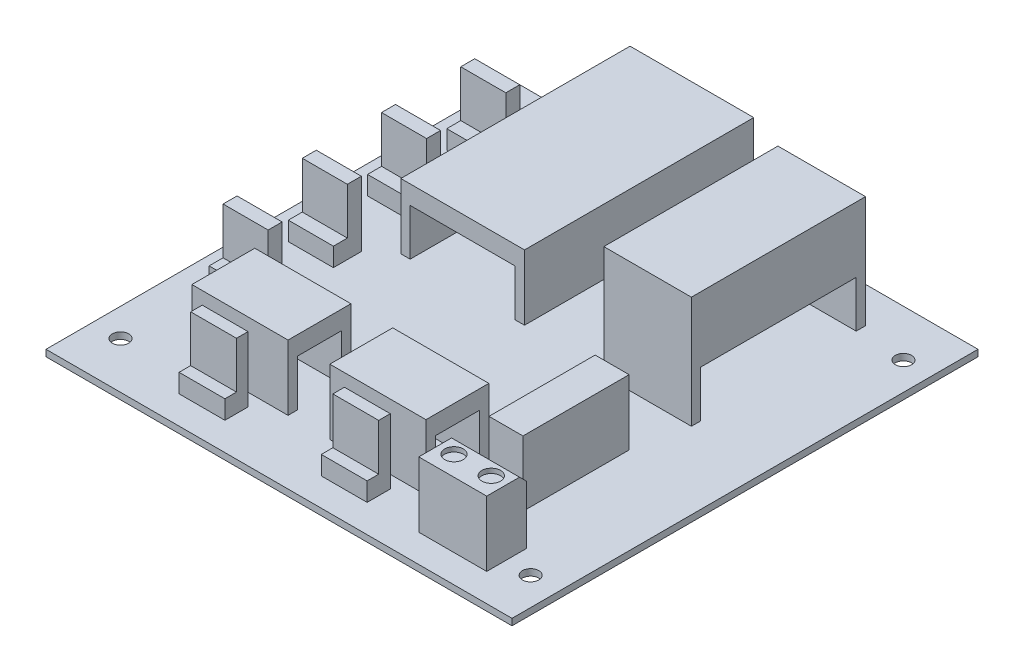
SolidWorks part; units mm, degrees
ref_plane "Plano frontal" through (0, 0, 0) normal (0, 0, 1) x (1, 0, 0)
ref_plane "Plano superior" through (0, 0, 0) normal (0, 1, 0) x (1, 0, 0)
ref_plane "Plano direito" through (0, 0, 0) normal (1, 0, 0) x (0, 0, -1)
sketch "Esboço1" plane through (0, 0, 0) normal (0, 1, 0) x (1, 0, 0)
  line L1 (50, -50) -> (-50, -50)
  line L2 (50, -50) -> (50, 50)
  line L3 (50, 50) -> (-50, 50)
  line L4 (-50, -50) -> (-50, 50)
  line L5 (50, -50) -> (-50, 50) construction
  line L6 (50, 50) -> (-50, -50) construction
  point P0 (0, 0)
  dimension "D1" = 100
extrude "Ressalto-extrusão1" add sketch "Esboço1" along normal blind 1.4
sketch "Esboço2" plane through (0, 1.4, 0) normal (0, 1, 0) x (1, 0, 0)
  line L0 (-50, 50) -> (-50, -50) construction
  line L1 (44, -44) -> (-44, -44)
  line L2 (44, -44) -> (44, 44)
  line L3 (44, 44) -> (-44, 44)
  line L4 (-44, -44) -> (-44, 44)
  line L5 (44, -44) -> (-44, 44) construction
  line L6 (44, 44) -> (-44, -44) construction
  line L7 (-50, -50) -> (50, -50) construction
  point P0 (0, 0)
  dimension "D1" = 6
  dimension "D2" = 6
extrude "Ressalto-extrusão2" add sketch "Esboço2" along normal blind 24
sketch "Esboço4" plane through (0, 25.4, 0) normal (0, 1, 0) x (1, 0, 0)
  line L0 (-44, -44) -> (44, -44) construction
  line L1 (38.5727, -44) -> (23.994, -44)
  line L2 (38.5727, -44) -> (38.5727, -35.4595)
  line L3 (38.5727, -35.4595) -> (23.994, -35.4595)
  line L4 (23.994, -44) -> (23.994, -35.4595)
  line L6 (23.994, -6.1504) -> (31.2833, -6.1504)
  line L7 (23.994, -6.1504) -> (23.994, -28.9295)
  line L8 (23.994, -28.9295) -> (31.2833, -28.9295)
  line L9 (31.2833, -6.1504) -> (31.2833, -28.9295)
  line L14 (14.7668, 42.2996) -> (33.5612, 42.2996)
  line L15 (14.7668, 42.2996) -> (14.7668, 4.9355)
  line L16 (14.7668, 4.9355) -> (33.5612, 4.9355)
  line L17 (33.5612, 42.2996) -> (33.5612, 4.9355)
  line L18 (-29.6701, 44) -> (-3.1234, 44)
  line L19 (-29.6701, 44) -> (-29.6701, 5.8111)
  line L20 (-29.6701, 5.8111) -> (-3.1234, 5.8111)
  line L21 (-3.1234, 44) -> (-3.1234, 5.8111)
  line L22 (44, 44) -> (-44, 44) construction
  line L23 (-32.3794, -22.8163) -> (-11.7467, -22.8163)
  line L24 (-32.3794, -22.8163) -> (-32.3794, -36.3118)
  line L25 (-32.3794, -36.3118) -> (-11.7467, -36.3118)
  line L26 (-11.7467, -22.8163) -> (-11.7467, -36.3118)
  line L27 (-2.7851, -22.8163) -> (17.8476, -22.8163)
  line L28 (-2.7851, -22.8163) -> (-2.7851, -36.3118)
  line L29 (-2.7851, -36.3118) -> (17.8476, -36.3118)
  line L30 (17.8476, -22.8163) -> (17.8476, -36.3118)
  line L31 (-44, 44) -> (-44, -44) construction
  line L32 (-50, 50) -> (50, 50)
  line L33 (-50, 50) -> (-50, -50)
  line L34 (-50, -50) -> (50, -50)
  line L35 (50, 50) -> (50, -50)
  line L36 (-44, 36) -> (-34.3294, 36)
  line L37 (-44, 36) -> (-44, 30)
  line L38 (-44, 30) -> (-34.3294, 30)
  line L39 (-34.3294, 36) -> (-34.3294, 30)
  line L40 (-44, 19) -> (-34.3294, 19)
  line L41 (-34.3294, 19) -> (-34.3294, 13)
  line L42 (-44, 13) -> (-34.3294, 13)
  line L43 (-44, 19) -> (-44, 13)
  line L44 (-44, 2) -> (-34.3294, 2)
  line L45 (-34.3294, 2) -> (-34.3294, -4)
  line L46 (-44, -4) -> (-34.3294, -4)
  line L47 (-44, 2) -> (-44, -4)
  line L48 (-44, -15) -> (-34.3294, -15)
  line L49 (-34.3294, -15) -> (-34.3294, -21)
  line L50 (-44, -21) -> (-34.3294, -21)
  line L51 (-44, -15) -> (-44, -21)
  line L52 (-44, -44) -> (44, -44) construction
  line L53 (-27.4417, -39.0319) -> (-17.6077, -39.0319)
  line L54 (-27.4417, -39.0319) -> (-27.4417, -44)
  line L55 (-27.4417, -44) -> (-17.6077, -44)
  line L56 (-17.6077, -39.0319) -> (-17.6077, -44)
  line L57 (-11.7467, -36.3118) -> (-2.7851, -36.3118) construction
  line L58 (-7.2659, -36.3118) -> (-7.2659, -44) construction
  line L59 (12.9099, -39.0319) -> (12.9099, -44)
  line L60 (12.9099, -44) -> (3.0759, -44)
  line L61 (3.0759, -39.0319) -> (3.0759, -44)
  line L62 (12.9099, -39.0319) -> (3.0759, -39.0319)
  line L63 (44, 44) -> (-44, 44) construction
  dimension "D1" = 4
  dimension "D2" = 8
  dimension "D3" = 6
  dimension "D4" = 11
extrude "Corte-extrusão1" cut sketch "Esboço4" against normal up to surface (24 mm away) up to face at (0, 1.4, 0)
sketch "Esboço5" plane through (0, 25.4, 0) normal (0, 1, 0) x (1, 0, 0)
  line L0 (23.994, -6.1504) -> (23.994, -28.9295) construction
  line L5 (23.994, -28.9295) -> (31.2833, -28.9295) construction
  line L6 (31.2833, -28.9295) -> (31.2833, -6.1504) construction
  line L7 (31.2833, -6.1504) -> (23.994, -6.1504) construction
  line L8 (-29.6701, 5.8111) -> (-3.1234, 5.8111)
  line L9 (-3.1234, 5.8111) -> (-3.1234, 44)
  line L10 (-3.1234, 44) -> (-29.6701, 44)
  line L11 (-29.6701, 44) -> (-29.6701, 5.8111)
  line L12 (-29.6701, 5.8111) -> (-3.1234, 5.8111)
  line L13 (-3.1234, 5.8111) -> (-3.1234, 44)
  line L14 (-3.1234, 44) -> (-29.6701, 44)
  line L15 (-29.6701, 44) -> (-29.6701, 5.8111)
  line L16 (-2.7851, -22.8163) -> (-2.7851, -36.3118) construction
  line L17 (-2.7851, -36.3118) -> (17.8476, -36.3118) construction
  line L18 (17.8476, -36.3118) -> (17.8476, -22.8163) construction
  line L19 (17.8476, -22.8163) -> (-2.7851, -22.8163) construction
  line L20 (-32.3794, -22.8163) -> (-32.3794, -36.3118) construction
  line L21 (-32.3794, -36.3118) -> (-11.7467, -36.3118) construction
  line L22 (-11.7467, -36.3118) -> (-11.7467, -22.8163) construction
  line L23 (-11.7467, -22.8163) -> (-32.3794, -22.8163) construction
  line L24 (23.994, -6.1504) -> (23.994, -28.9295)
  line L25 (23.994, -28.9295) -> (31.2833, -28.9295)
  line L26 (31.2833, -28.9295) -> (31.2833, -6.1504)
  line L27 (31.2833, -6.1504) -> (23.994, -6.1504)
  line L28 (-2.7851, -22.8163) -> (-2.7851, -36.3118)
  line L29 (-2.7851, -36.3118) -> (17.8476, -36.3118)
  line L30 (17.8476, -36.3118) -> (17.8476, -22.8163)
  line L31 (17.8476, -22.8163) -> (-2.7851, -22.8163)
  line L32 (-32.3794, -22.8163) -> (-32.3794, -36.3118)
  line L33 (-32.3794, -36.3118) -> (-11.7467, -36.3118)
  line L34 (-11.7467, -36.3118) -> (-11.7467, -22.8163)
  line L35 (-11.7467, -22.8163) -> (-32.3794, -22.8163)
  line L36 (-44, -15) -> (-44, -21) construction
  line L37 (-44, -21) -> (-34.3294, -21) construction
  line L38 (-34.3294, -21) -> (-34.3294, -15) construction
  line L39 (-34.3294, -15) -> (-44, -15) construction
  line L40 (38.5727, -35.4595) -> (23.994, -35.4595)
  line L41 (23.994, -35.4595) -> (23.994, -44)
  line L42 (23.994, -44) -> (38.5727, -44)
  line L43 (38.5727, -44) -> (38.5727, -35.4595)
  line L44 (38.5727, -35.4595) -> (23.994, -35.4595)
  line L45 (23.994, -35.4595) -> (23.994, -44)
  line L46 (23.994, -44) -> (38.5727, -44)
  line L47 (38.5727, -44) -> (38.5727, -35.4595)
  line L48 (-44, 2) -> (-44, -4) construction
  line L49 (-44, -4) -> (-34.3294, -4) construction
  line L50 (-34.3294, -4) -> (-34.3294, 2) construction
  line L51 (-34.3294, 2) -> (-44, 2) construction
  line L52 (-44, 19) -> (-44, 13) construction
  line L53 (-44, 13) -> (-34.3294, 13) construction
  line L54 (-34.3294, 13) -> (-34.3294, 19) construction
  line L55 (-34.3294, 19) -> (-44, 19) construction
  line L56 (-44, 36) -> (-44, 30) construction
  line L57 (-44, 30) -> (-34.3294, 30) construction
  line L58 (-34.3294, 30) -> (-34.3294, 36) construction
  line L59 (-34.3294, 36) -> (-44, 36) construction
  line L60 (-44, -15) -> (-44, -21)
  line L61 (-44, -21) -> (-34.3294, -21)
  line L62 (-34.3294, -21) -> (-34.3294, -15)
  line L63 (-34.3294, -15) -> (-44, -15)
  line L64 (-44, 2) -> (-44, -4)
  line L65 (-44, -4) -> (-34.3294, -4)
  line L66 (-34.3294, -4) -> (-34.3294, 2)
  line L67 (-34.3294, 2) -> (-44, 2)
  line L68 (-44, 19) -> (-44, 13)
  line L69 (-44, 13) -> (-34.3294, 13)
  line L70 (-34.3294, 13) -> (-34.3294, 19)
  line L71 (-34.3294, 19) -> (-44, 19)
  line L72 (-44, 36) -> (-44, 30)
  line L73 (-44, 30) -> (-34.3294, 30)
  line L74 (-34.3294, 30) -> (-34.3294, 36)
  line L75 (-34.3294, 36) -> (-44, 36)
  line L76 (12.9099, -39.0319) -> (3.0759, -39.0319) construction
  line L77 (3.0759, -39.0319) -> (3.0759, -44) construction
  line L78 (3.0759, -44) -> (12.9099, -44) construction
  line L79 (12.9099, -44) -> (12.9099, -39.0319) construction
  line L80 (-27.4417, -44) -> (-17.6077, -44) construction
  line L81 (-17.6077, -44) -> (-17.6077, -39.0319) construction
  line L82 (-17.6077, -39.0319) -> (-27.4417, -39.0319) construction
  line L83 (-27.4417, -39.0319) -> (-27.4417, -44) construction
  line L84 (12.9099, -39.0319) -> (3.0759, -39.0319)
  line L85 (3.0759, -39.0319) -> (3.0759, -44)
  line L86 (3.0759, -44) -> (12.9099, -44)
  line L87 (12.9099, -44) -> (12.9099, -39.0319)
  line L88 (-27.4417, -44) -> (-17.6077, -44)
  line L89 (-17.6077, -44) -> (-17.6077, -39.0319)
  line L90 (-17.6077, -39.0319) -> (-27.4417, -39.0319)
  line L91 (-27.4417, -39.0319) -> (-27.4417, -44)
  dimension "D1" = 0
  dimension "D2" = 0
extrude "Corte-extrusão2" cut sketch "Esboço5" against normal blind 10
sketch "Esboço6" plane through (0, 15.4, 0) normal (0, 1, 0) x (1, 0, 0)
  line L0 (23.994, -39.7298) -> (38.5727, -39.7298) construction
  line L1 (23.994, -35.4595) -> (23.994, -44) construction
  line L2 (38.5727, -44) -> (38.5727, -35.4595) construction
  circle A0 centre (27.2833, -39.7298) radius 2
  circle A1 centre (35.2833, -39.7298) radius 2
  point P10 (31.2833, -39.7298)
  dimension "D1" = 4
  dimension "D2" = 8
  dimension "D3" = 4
extrude "Corte-extrusão3" cut sketch "Esboço6" against normal blind 1
chamfer "Chanfro1" distance 1.5 angle 45 1 edges at (31.2833, 15.4, 35.4595)
sketch "Esboço7" plane through (33.5612, 0, 0) normal (1, 0, 0) x (0, 0, -1)
  line L0 (42.2996, 1.4) -> (4.9355, 1.4) construction
  line L1 (6.9355, 1.4) -> (40.2996, 1.4)
  line L2 (6.9355, 1.4) -> (6.9355, 11.4)
  line L3 (6.9355, 11.4) -> (40.2996, 11.4)
  line L4 (40.2996, 1.4) -> (40.2996, 11.4)
  line L5 (4.9355, 1.4) -> (4.9355, 25.4) construction
  line L6 (42.2996, 1.4) -> (42.2996, 25.4) construction
  dimension "D1" = 2
  dimension "D2" = 10
  dimension "D3" = 2
extrude "Corte-extrusão4" cut sketch "Esboço7" against normal up to next
sketch "Esboço8" plane through (0, 0, -44) normal (0, 0, -1) x (-1, 0, 0)
  line L0 (-50, 1.4) -> (50, 1.4) construction
  line L1 (5.1234, 1.4) -> (27.6701, 1.4)
  line L2 (5.1234, 1.4) -> (5.1234, 11.4007)
  line L3 (5.1234, 11.4007) -> (27.6701, 11.4007)
  line L4 (27.6701, 1.4) -> (27.6701, 11.4007)
  line L5 (3.1234, 1.4) -> (3.1234, 15.4) construction
  line L6 (29.6701, 1.4) -> (29.6701, 15.4) construction
  dimension "D1" = 2
  dimension "D2" = 2
  dimension "D3" = 10.0007
extrude "Corte-extrusão5" cut sketch "Esboço8" against normal up to next
sketch "Esboço9" plane through (-32.3794, 0, 0) normal (-1, 0, 0) x (0, 0, 1)
  line L0 (-50, 1.4) -> (50, 1.4) construction
  line L1 (24.8163, 1.4) -> (34.3118, 1.4)
  line L2 (24.8163, 1.4) -> (24.8163, 11.4)
  line L3 (24.8163, 11.4) -> (34.3118, 11.4)
  line L4 (34.3118, 1.4) -> (34.3118, 11.4)
  line L5 (22.8163, 1.4) -> (22.8163, 15.4) construction
  line L6 (36.3118, 1.4) -> (36.3118, 15.4) construction
  dimension "D1" = 2
  dimension "D2" = 2
  dimension "D3" = 10
extrude "Corte-extrusão6" cut sketch "Esboço9" against normal up to surface (50.227 mm away) up to face at (17.8476, 8.4, 29.5641)
sketch "Esboço10" plane through (-34.3294, 0, 0) normal (-1, 0, 0) x (0, 0, 1)
  line L0 (-36, 15.4) -> (-30, 15.4) construction
  line L1 (-33, 15.4) -> (-30, 15.4)
  line L2 (-33, 15.4) -> (-33, 5.4)
  line L3 (-33, 5.4) -> (-30, 5.4)
  line L4 (-30, 15.4) -> (-30, 5.4)
  line L5 (-30, 1.4) -> (-30, 15.4) construction
  line L6 (-19, 15.4) -> (-13, 15.4) construction
  line L7 (-16, 15.4) -> (-13, 15.4)
  line L8 (-16, 15.4) -> (-16, 5.4)
  line L9 (-16, 5.4) -> (-13, 5.4)
  line L10 (-13, 15.4) -> (-13, 5.4)
  line L11 (-13, 1.4) -> (-13, 15.4) construction
  line L12 (-2, 15.4) -> (4, 15.4) construction
  line L13 (1, 15.4) -> (4, 15.4)
  line L14 (1, 15.4) -> (1, 5.4)
  line L15 (1, 5.4) -> (4, 5.4)
  line L16 (4, 15.4) -> (4, 5.4)
  line L17 (4, 1.4) -> (4, 15.4) construction
  line L18 (15, 15.4) -> (21, 15.4) construction
  line L19 (18, 15.4) -> (21, 15.4)
  line L20 (18, 15.4) -> (18, 5.4)
  line L21 (18, 5.4) -> (21, 5.4)
  line L22 (21, 15.4) -> (21, 5.4)
  line L23 (21, 1.4) -> (21, 15.4) construction
  dimension "D1" = 10
extrude "Corte-extrusão7" cut sketch "Esboço10" along normal up to surface (9.6706 mm away) up to face at (-44, 8.4, 18)
sketch "Esboço11" plane through (-27.4417, 0, 0) normal (-1, 0, 0) x (0, 0, 1)
  line L0 (39.0319, 15.4) -> (44, 15.4) construction
  line L1 (41.5159, 15.4) -> (44, 15.4)
  line L2 (41.5159, 15.4) -> (41.5159, 5.4)
  line L3 (41.5159, 5.4) -> (44, 5.4)
  line L4 (44, 15.4) -> (44, 5.4)
  line L5 (44, 1.4) -> (44, 15.4) construction
  dimension "D1" = 10
extrude "Corte-extrusão8" cut sketch "Esboço11" against normal up to surface (40.3517 mm away) up to face at (12.9099, 8.4, 41.5159)
sketch "Esboço12" plane through (0, 0, 0) normal (0, -1, 0) x (1, 0, 0)
  line L0 (-50, -50) -> (-50, 50) construction
  line L1 (44, -40) -> (-44, -40) construction
  line L2 (44, -40) -> (44, 40) construction
  line L3 (44, 40) -> (-44, 40) construction
  line L4 (-44, -40) -> (-44, 40) construction
  line L5 (44, -40) -> (-44, 40) construction
  line L6 (44, 40) -> (-44, -40) construction
  line L7 (-50, 50) -> (50, 50) construction
  circle A0 centre (-44, 40) radius 1.75
  circle A1 centre (44, 40) radius 1.75
  circle A2 centre (44, -40) radius 1.75
  circle A3 centre (-44, -40) radius 1.75
  point P0 (0, 0)
  dimension "D3" = 3.5
  dimension "D1" = 6
  dimension "D2" = 10
extrude "Corte-extrusão9" cut sketch "Esboço12" against normal up to surface (1.4 mm away) up to face at (-22.0631, 1.4, 35.3118)
sketch "Esboço13" plane through (0, 0, -44) normal (0, 0, -1) x (-1, 0, 0)
  line L8 (5.1234, 11.4007) -> (27.6701, 11.4007)
  line L9 (27.6701, 11.4007) -> (27.6701, 1.4)
  line L10 (27.6701, 1.4) -> (29.6701, 1.4)
  line L11 (29.6701, 1.4) -> (29.6701, 15.4)
  line L12 (29.6701, 15.4) -> (3.1234, 15.4)
  line L13 (3.1234, 15.4) -> (3.1234, 1.4)
  line L14 (3.1234, 1.4) -> (5.1234, 1.4)
  line L15 (5.1234, 1.4) -> (5.1234, 11.4007)
  line L16 (5.1234, 11.4007) -> (27.6701, 11.4007)
  line L17 (27.6701, 11.4007) -> (27.6701, 1.4)
  line L18 (27.6701, 1.4) -> (29.6701, 1.4)
  line L19 (29.6701, 1.4) -> (29.6701, 15.4)
  line L20 (29.6701, 15.4) -> (3.1234, 15.4)
  line L21 (3.1234, 15.4) -> (3.1234, 1.4)
  line L22 (3.1234, 1.4) -> (5.1234, 1.4)
  line L23 (5.1234, 1.4) -> (5.1234, 11.4007)
  dimension "D1" = 0
extrude "Ressalto-extrusão3" add sketch "Esboço13" along normal blind 11
